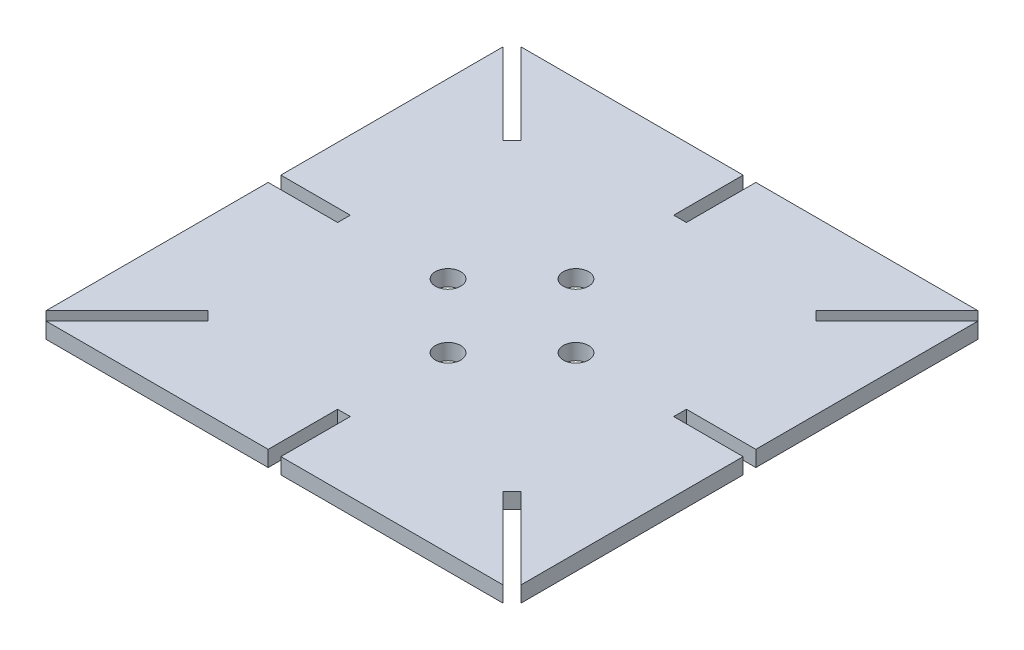
SolidWorks part; units mm, degrees
ref_plane "前视基准面" through (0, 0, 0) normal (0, 0, 1) x (1, 0, 0)
ref_plane "上视基准面" through (0, 0, 0) normal (0, 1, 0) x (1, 0, 0)
ref_plane "右视基准面" through (0, 0, 0) normal (1, 0, 0) x (0, 0, -1)
sketch "草图1" plane through (0, 0, 0) normal (0, 1, 0) x (1, 0, 0)
  line L4 (0, 0) -> (-30, 0) construction
  line L5 (0, 0) -> (-30, 30) construction
  line L12 (-30, 0.8) -> (-21.23, 0.8)
  line L17 (-21.23, 0.8) -> (-21.23, -0.8)
  line L22 (-18.6275, 19.7588) -> (-19.7588, 18.6275)
  line L26 (-19.7588, 18.6275) -> (-30, 28.8686)
  line L27 (-30, -0.8) -> (-21.23, -0.8)
  line L28 (-18.6275, 19.7588) -> (-28.8686, 30)
  line L29 (19.7588, 18.6275) -> (18.6275, 19.7588)
  line L30 (18.6275, 19.7588) -> (28.8686, 30)
  line L31 (19.7588, 18.6275) -> (30, 28.8686)
  line L32 (0.8, 30) -> (0.8, 21.23)
  line L33 (0.8, 21.23) -> (-0.8, 21.23)
  line L34 (-0.8, 30) -> (-0.8, 21.23)
  line L35 (18.6275, -19.7588) -> (19.7588, -18.6275)
  line L36 (19.7588, -18.6275) -> (30, -28.8686)
  line L37 (18.6275, -19.7588) -> (28.8686, -30)
  line L38 (30, -0.8) -> (21.23, -0.8)
  line L39 (21.23, -0.8) -> (21.23, 0.8)
  line L40 (30, 0.8) -> (21.23, 0.8)
  line L41 (-19.7588, -18.6275) -> (-18.6275, -19.7588)
  line L42 (-18.6275, -19.7588) -> (-28.8686, -30)
  line L43 (-19.7588, -18.6275) -> (-30, -28.8686)
  line L44 (-30, -30) -> (-30, 30)
  line L45 (30, -30) -> (-30, -30)
  line L46 (30, 30) -> (30, -30)
  line L47 (-30, 30) -> (30, 30)
  line L48 (-0.8, -30) -> (-0.8, -21.23)
  line L49 (-0.8, -21.23) -> (0.8, -21.23)
  line L50 (0.8, -30) -> (0.8, -21.23)
  circle A4 centre (8.08, 0) radius 1.6
  circle A5 centre (0, -8.08) radius 1.6
  circle A6 centre (-8.08, 0) radius 1.6
  circle A7 centre (0, 8.08) radius 1.6
  point P7 (0, 0)
  point P10 (-21.23, 0)
  point P12 (-19.1931, 19.1931)
  point P13 (0.8, 21.23)
  point P22 (0, 21.23)
  point P24 (19.1931, 19.1931)
  point P32 (21.23, 0)
  point P34 (19.1931, -19.1931)
  point P42 (0, -21.23)
  point P44 (-19.1931, -19.1931)
  point P45 (0, 0)
  point P73 (0, 0.001)
  point P74 (0.001, 0.001)
  point P75 (0.001, 0)
  dimension "D1" = 0.8
  dimension "D2" = 14.4832
  dimension "D4" = 8.77
  dimension "D5" = 4
  dimension "D3" = 0.8
extrude "凸台-拉伸1" add sketch "草图1" along normal blind 2 contours L50 L45 L37 L35 L36 L46 L38 L39 L40 L31 L29 L30 L47 L32 L33 L34 L28 L22 L26 L44 L12 L17 L27 L43 L41 L42 L48 L49 A7 A6 A5 A4
